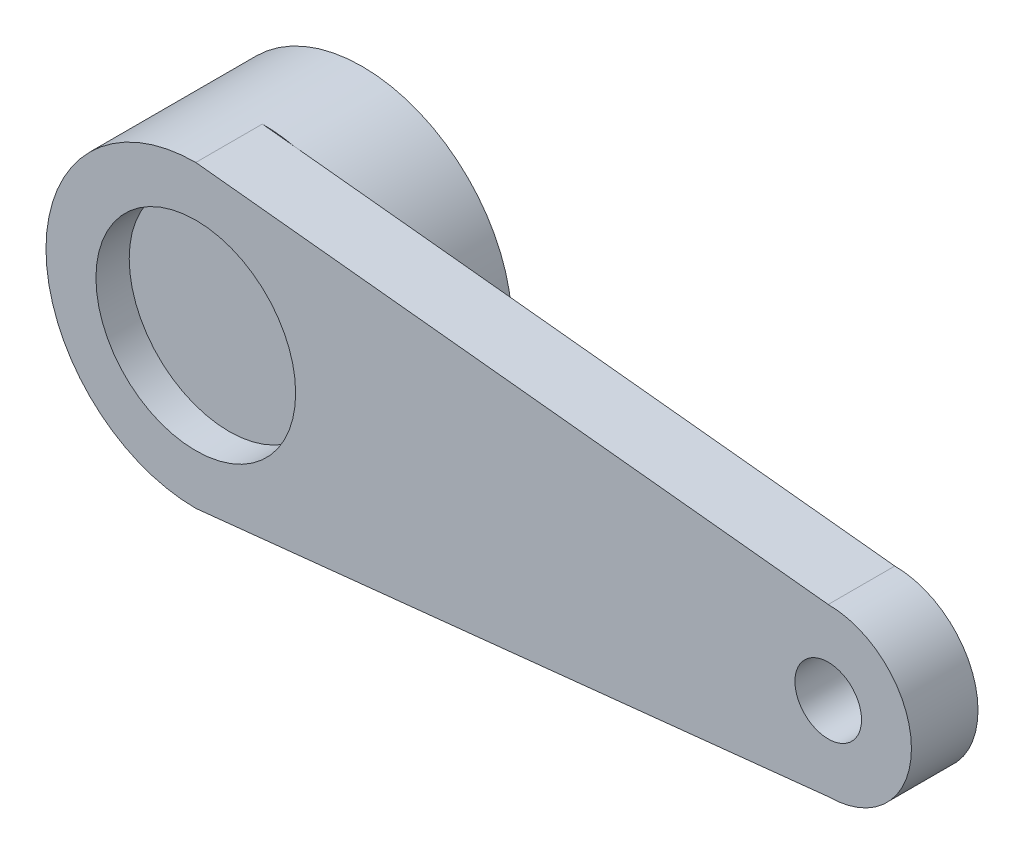
SolidWorks part; units mm, degrees
ref_plane "Płaszczyzna przednia" through (0, 0, 0) normal (0, 0, 1) x (1, 0, 0)
ref_plane "Płaszczyzna górna" through (0, 0, 0) normal (0, 1, 0) x (1, 0, 0)
ref_plane "Płaszczyzna prawa" through (0, 0, 0) normal (1, 0, 0) x (0, 0, -1)
sketch "Sketch1" plane through (0, 0, 0) normal (0, 0, 1) x (1, 0, 0)
  line L0 (-12.5588, 2.8322) -> (6.4412, 2.8322)
  line L1 (-12.5588, 7.3322) -> (6.4412, 5.3322)
  line L2 (-12.5588, -1.6678) -> (6.4412, 0.3322)
  circle A0 centre (-12.5588, 2.8322) radius 4.5
  circle A1 centre (6.4412, 2.8322) radius 2.5
  dimension "D1" = 19
extrude "Boss-Extrude1" add sketch "Sketch1" along normal blind 2
sketch "Sketch3" plane through (0, 0, 2) normal (0, 0, 1) x (1, 0, 0)
  circle A0 centre (6.4412, 2.8322) radius 1
extrude "Cut-Extrude1" cut sketch "Sketch3" against normal blind 3
sketch "Sketch4" plane through (0, 0, 0) normal (0, 0, -1) x (-1, 0, 0)
  circle A0 centre (12.5588, 2.8322) radius 4.5
extrude "Boss-Extrude3" add sketch "Sketch4" along normal blind 3 contours A0
sketch "Sketch5" plane through (0, 0, 2) normal (0, 0, 1) x (1, 0, 0)
  circle A0 centre (-12.5588, 2.8322) radius 3
extrude "Cut-Extrude2" cut sketch "Sketch5" against normal blind 1
